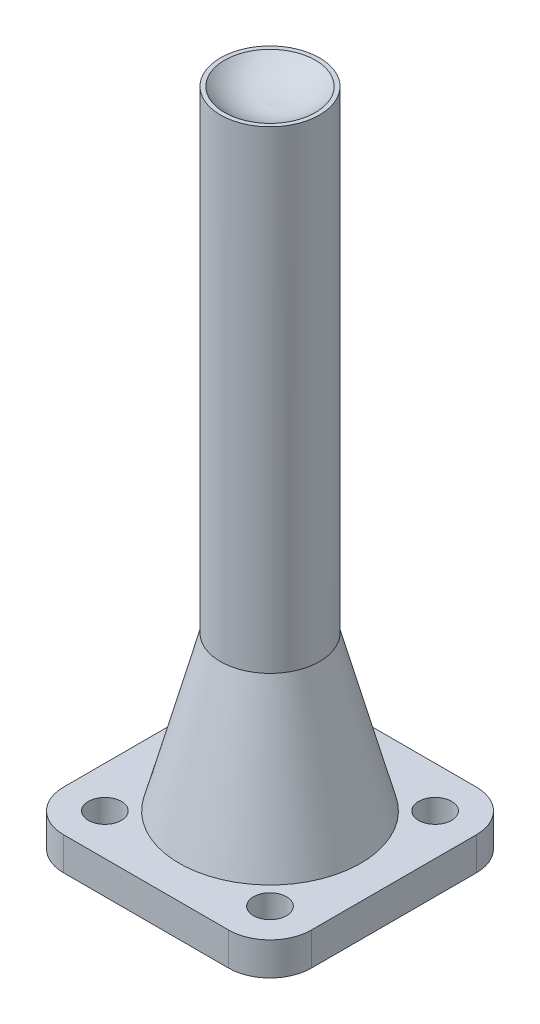
SolidWorks part; units mm, degrees
ref_plane "Спереди" through (0, 0, 0) normal (0, 0, 1) x (1, 0, 0)
ref_plane "Сверху" through (0, 0, 0) normal (0, 1, 0) x (1, 0, 0)
ref_plane "Справа" through (0, 0, 0) normal (1, 0, 0) x (0, 0, -1)
sketch "Эскиз1" plane through (0, 0, 0) normal (0, 1, 0) x (1, 0, 0)
  line L1 (-15, -15) -> (15, -15)
  line L2 (-15, -15) -> (-15, 15)
  line L3 (-15, 15) -> (15, 15)
  line L4 (15, -15) -> (15, 15)
  line L5 (0, 15) -> (0, -15) construction
  line L6 (-15, 0) -> (15, 0) construction
  line L7 (-10, -10) -> (10, -10) construction
  line L8 (-10, -10) -> (-10, 10) construction
  line L9 (-10, 10) -> (10, 10) construction
  line L10 (10, -10) -> (10, 10) construction
  line L11 (0, 10) -> (0, -10) construction
  line L12 (-10, 0) -> (10, 0) construction
  circle A0 centre (-10, 10) radius 2
  circle A1 centre (10, 10) radius 2
  circle A2 centre (10, -10) radius 2
  circle A3 centre (-10, -10) radius 2
  point P0 (0, 0)
  point P4 (0, 0)
  dimension "D5" = 4
  dimension "D1" = 30
  dimension "D2" = 30
  dimension "D3" = 20
  dimension "D4" = 20
extrude "Бобышка-Вытянуть1" add sketch "Эскиз1" along normal blind 4
fillet "Скругление1" radius 5 4 edges at (15, 2, 15) (-15, 2, -15) (15, 2, -15) (-15, 2, 15)
sketch "Эскиз2" plane through (0, 4, 0) normal (0, 1, 0) x (1, 0, 0)
  circle A0 centre (0, 0) radius 6
  dimension "D1" = 12
extrude "Бобышка-Вытянуть2" add sketch "Эскиз2" along normal blind 76
ref_plane "Плоскость1" through (0, 0, 0) normal (0, 0, 1) x (1, 0, 0)
sketch "Эскиз7" plane through (0, 0, 0) normal (0, 0, 1) x (1, 0, 0)
  line L0 (0, 82.4047) -> (0, 78) construction
  line L1 (0, 78) -> (9.0963, 78) construction
  line L2 (6, 80) -> (-6, 80) construction
  line L3 (5.5, 80) -> (0, 80)
  line L4 (0, 80) -> (0, 78)
  arc A0 (0, 78) -> (0.0893, 78) centre (0.0447, 78) ccw
  arc A1 (5.5, 80) -> (0, 78) centre (0.6855, 84.6775) cw
  point P11 (0, 0)
  point P12 (-2.7349, 84.5436)
  point P13 (0, 0)
  point P14 (-2.7349, 84.5436)
  dimension "D1" = 2
  dimension "D2" = 5.5
revolve "Вырез-Повернуть3" cut sketch "Эскиз7" angle 360 about L0
chamfer "Фаска1" distance 5 angle 75 1 edges at (0, 4, 6)
sketch "Эскиз5" plane through (0, 0, 0) normal (0, -1, 0) x (1, 0, 0)
  line L1 (-16.5147, -16.1651) -> (16.5147, -16.1651)
  line L2 (-16.5147, -16.1651) -> (-16.5147, 16.1651)
  line L3 (-16.5147, 16.1651) -> (16.5147, 16.1651)
  line L4 (16.5147, -16.1651) -> (16.5147, 16.1651)
  line L5 (0, 16.1651) -> (0, -16.1651) construction
  line L6 (-16.5147, 0) -> (16.5147, 0) construction
  point P0 (0, 0)
extrude "Вырез-Вытянуть2" [suppressed] cut sketch "Эскиз5" against normal blind 70
